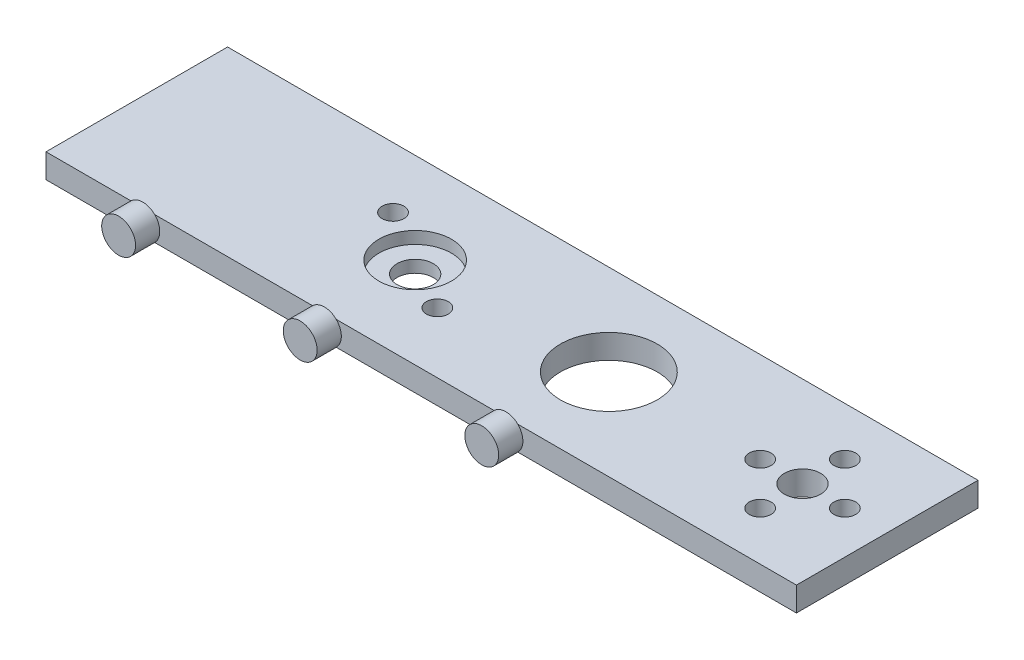
SolidWorks part; units mm, degrees
ref_plane "前视基准面" through (0, 0, 0) normal (0, 0, 1) x (1, 0, 0)
ref_plane "上视基准面" through (0, 0, 0) normal (0, 1, 0) x (1, 0, 0)
ref_plane "右视基准面" through (0, 0, 0) normal (1, 0, 0) x (0, 0, -1)
other "Configuration Table"
sketch "草图1" plane through (0, 0, 0) normal (0, 1, 0) x (1, 0, 0)
  line L0 (-31, 7.5) -> (31, 7.5)
  line L1 (31, 7.5) -> (31, -7.5)
  line L2 (31, -7.5) -> (-31, -7.5)
  line L3 (-31, -7.5) -> (-31, 7.5)
  line L4 (-31, 0) -> (31, 0) construction
  line L5 (-12.3301, -2.5) -> (-3.6699, 2.5) construction
  line L6 (-12.8083, -5.95) -> (-3.1917, -5.95) construction
  line L7 (-12.8083, 5.95) -> (-3.1917, 5.95) construction
  line L8 (-8, 7.5) -> (-8, -7.5) construction
  circle A0 centre (-8, 0) radius 1.5
  circle A1 centre (-3.6699, 2.5) radius 0.9
  circle A3 centre (-12.3301, -2.5) radius 0.9
  arc A4 (-12.8083, 5.95) -> (-12.8083, -5.95) centre (-8, 0) ccw construction
  circle A5 centre (8, 0) radius 4
  arc A6 (-3.1917, -5.95) -> (-3.1917, 5.95) centre (-8, 0) ccw construction
  circle A7 centre (24, 0) radius 1.5
  circle A8 centre (24, 0) radius 3.5 construction
  circle A9 centre (27.5, 0) radius 0.9
  circle A10 centre (24, -3.5) radius 0.9
  circle A11 centre (20.5, 0) radius 0.9
  circle A12 centre (24, 3.5) radius 0.9
  circle A13 centre (-12.3301, 2.5) radius 0.9
  circle A14 centre (-3.6699, -2.5) radius 0.9
  point P5 (0, 7.5)
  point P7 (-31, 0)
  dimension "D3" = 3
  dimension "D6" = 1.8
  dimension "D9" = 15.3
  dimension "D12" = 8
  dimension "D14" = 3
  dimension "D15" = 7
  dimension "D16" = 1.8
  dimension "D1" = 62
  dimension "D2" = 15
  dimension "D4" = 23
  dimension "D7" = 30
  dimension "D8" = 10
  dimension "D10" = 11.9
  dimension "D11" = 16
  dimension "D13" = 16
  dimension "D5" = 2
  dimension "D17" = 4
extrude "凸台-拉伸1" add sketch "草图1" along normal blind 2 contours L3 L2 L1 L0 A13 A12 A11 A10 A9 A7 A5 A3 A1 A0 A14 | A3 | A1
sketch "草图2" plane through (0, 0, 7.5) normal (0, 0, 1) x (1, 0, 0)
  line L0 (-31, 1) -> (31, 1) construction
  line L1 (-31, 2) -> (-31, 0) construction
  line L2 (31, 2) -> (31, 0) construction
  circle A0 centre (-23, 1) radius 1.4
  circle A1 centre (-8, 1) radius 1.4
  circle A2 centre (7, 1) radius 1.4
  dimension "D1" = 2.8
  dimension "D2" = 2.8
  dimension "D3" = 2.8
  dimension "D4" = 15
  dimension "D5" = 15
  dimension "D6" = 8
extrude "凸台-拉伸2" add sketch "草图2" along normal blind 2
sketch "草图3" plane through (0, 2, 0) normal (0, 1, 0) x (1, 0, 0)
  text T0 "R" font "Microsoft YaHei UI" height 3.5
sketch "草图4" plane through (0, 2, 0) normal (0, 1, 0) x (1, 0, 0)
  circle A0 centre (-8, 0) radius 3
  dimension "D1" = 6
extrude "切除-拉伸1" cut sketch "草图4" against normal blind 1
